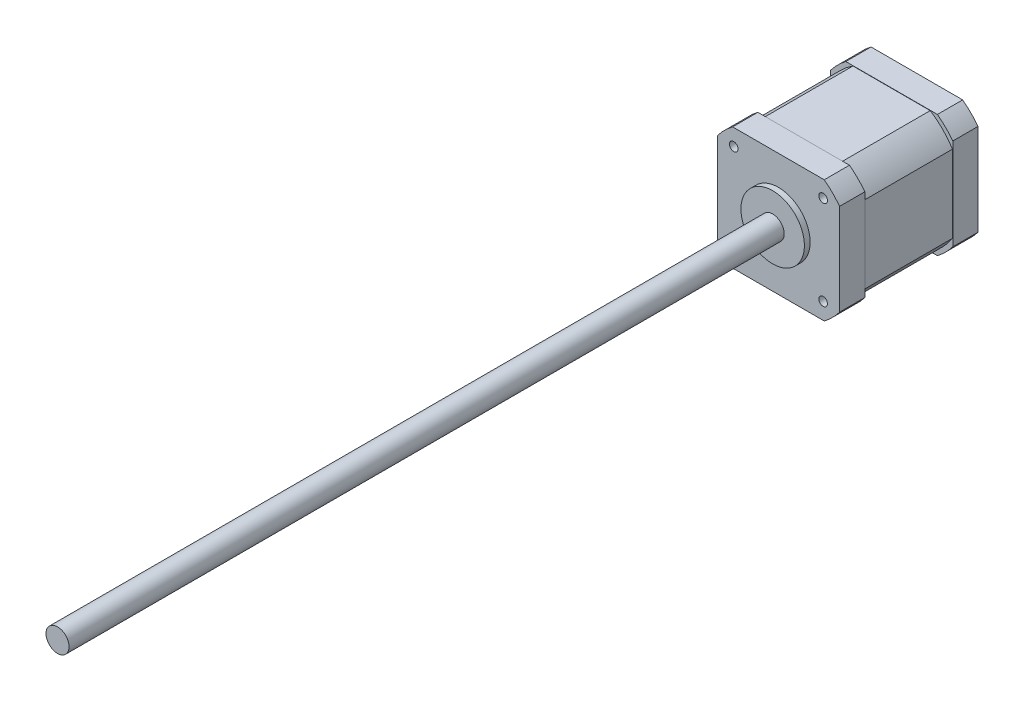
SolidWorks part; units mm, degrees
material "Plain Carbon Steel"
ref_plane "Front" through (0, 0, 0) normal (0, 0, 1) x (1, 0, 0)
ref_plane "Top" through (0, 0, 0) normal (0, 1, 0) x (1, 0, 0)
ref_plane "Right" through (0, 0, 0) normal (1, 0, 0) x (0, 0, -1)
sketch "Sketch1" plane through (0, 0, 0) normal (0, 0, 1) x (1, 0, 0)
  circle A0 centre (0, 0) radius 4
  dimension "D1" = 8
extrude "Boss-Extrude1" add sketch "Sketch1" along normal blind 250
sketch "Sketch2" plane through (0, 0, 0) normal (0, 0, -1) x (-1, 0, 0)
  circle A0 centre (0, 0) radius 11
  dimension "D1" = 22
extrude "Boss-Extrude2" add sketch "Sketch2" against normal blind 2
sketch "Sketch3" plane through (0, 0, 0) normal (0, 0, -1) x (-1, 0, 0)
  line L1 (21.209, -21.209) -> (-21.209, -21.209)
  line L2 (21.209, -21.209) -> (21.209, 21.209)
  line L3 (21.209, 21.209) -> (-21.209, 21.209)
  line L4 (-21.209, -21.209) -> (-21.209, 21.209)
  line L5 (21.209, -21.209) -> (-21.209, 21.209) construction
  line L6 (21.209, 21.209) -> (-21.209, -21.209) construction
  point P0 (0, 0)
  dimension "D1" = 42.418
extrude "Boss-Extrude3" add sketch "Sketch3" along normal blind 48
sketch "Sketch4" plane through (0, 0, -48) normal (0, 0, -1) x (-1, 0, 0)
  line L0 (-21.209, -15.888) -> (-21.209, -21.209)
  line L1 (15.888, -21.209) -> (21.209, -21.209)
  line L2 (21.209, 15.888) -> (21.209, 21.209)
  line L3 (-15.888, 21.209) -> (-21.209, 21.209)
  line L4 (-21.209, 21.209) -> (-21.209, -21.209)
  line L5 (-21.209, -21.209) -> (21.209, -21.209)
  line L6 (21.209, -21.209) -> (21.209, 21.209)
  line L7 (21.209, 21.209) -> (-21.209, 21.209)
  line L8 (-21.209, 21.209) -> (-21.209, 15.888)
  line L9 (-21.209, -21.209) -> (-15.888, -21.209)
  line L10 (21.209, -21.209) -> (21.209, -15.888)
  line L11 (21.209, 21.209) -> (15.888, 21.209)
  arc A0 (-21.209, -15.888) -> (-15.888, -21.209) centre (0, 0) ccw
  arc A1 (15.888, -21.209) -> (21.209, -15.888) centre (0, 0) ccw
  arc A2 (21.209, 15.888) -> (15.888, 21.209) centre (0, 0) ccw
  arc A3 (-15.888, 21.209) -> (-21.209, 15.888) centre (0, 0) ccw
  dimension "D2" = 26.5
  dimension "D1" = 0
extrude "Cut-Extrude1" cut sketch "Sketch4" against normal through all
hole_wizard "M3x0.5 Tapped Hole1" positions "Sketch6" profile "Sketch5" tap size "M3x0.5" standard "ANSI Metric"
sketch "Sketch6" plane through (0, 0, 0) normal (0, 0, 1) x (1, 0, 0)
  line L0 (-16.1632, 0) -> (0, 0) construction
  line L1 (0, 0) -> (0, 15.0764) construction
  point P0 (-15.5, 15.5)
  point P11 (-15.5, -15.5)
  point P12 (15.5, -15.5)
  point P13 (15.5, 15.5)
  dimension "D1" = 31
  dimension "D2" = 31
sketch "Sketch5" plane through (-15.5, 15.5, 0) normal (1, 0, 0) x (0, -1, 0)
  line L0 (0, 0) -> (0, 8.2511)
  line L1 (0, 8.2511) -> (1.25, 7.5)
  line L2 (1.25, 7.5) -> (1.25, 6)
  line L3 (1.25, 6) -> (1.5, 6)
  line L4 (1.5, 6) -> (1.5, 0)
  line L5 (1.5, 0) -> (0, 0)
  line L10 (0, 8.2511) -> (-1.25, 7.5) construction
  line L11 (0, -6.35) -> (0, 107.95) construction
  dimension "Tap Drill Dia." = 2.5
  dimension "Tap Drill Depth" = 7.5
  dimension "Thread Major Dia." = 3
  dimension "Thread Depth" = 6
  dimension "Drill Angle" = 118
ref_plane "Plane1" through (0, 0, -24) normal (0, 0, 1) x (1, 0, 0)
sketch "Sketch8" plane through (0, 0, -24) normal (0, 0, 1) x (1, 0, 0)
  line L0 (-13.3944, 21.109) -> (13.3944, 21.109)
  line L1 (-5.7152, 0) -> (0, 0) construction
  line L2 (0, 0) -> (0, 8.4579) construction
  line L3 (-15.888, 21.209) -> (15.888, 21.209) construction
  line L4 (-13.3944, -21.109) -> (13.3944, -21.109)
  line L5 (-21.109, 13.3944) -> (-21.109, -13.3944)
  line L6 (-21.209, -15.888) -> (-21.209, 15.888) construction
  line L7 (21.109, 13.3944) -> (21.109, -13.3944)
  line L12 (15.888, 21.209) -> (-15.888, 21.209)
  line L13 (-21.209, 15.888) -> (-21.209, -15.888)
  line L14 (-15.888, -21.209) -> (15.888, -21.209)
  line L15 (21.209, -15.888) -> (21.209, 15.888)
  line L16 (15.888, 21.209) -> (-15.888, 21.209)
  line L17 (-21.209, 15.888) -> (-21.209, -15.888)
  line L18 (-15.888, -21.209) -> (15.888, -21.209)
  line L19 (21.209, -15.888) -> (21.209, 15.888)
  arc A0 (-13.3944, 21.109) -> (-21.109, 13.3944) centre (0, 0) ccw
  arc A1 (-21.109, -13.3944) -> (-13.3944, -21.109) centre (0, 0) ccw
  arc A2 (21.109, 13.3944) -> (13.3944, 21.109) centre (0, 0) ccw
  arc A3 (13.3944, -21.109) -> (21.109, -13.3944) centre (0, 0) ccw
  arc A5 (-15.888, 21.209) -> (-21.209, 15.888) centre (0, 0) ccw
  arc A6 (-21.209, -15.888) -> (-15.888, -21.209) centre (0, 0) ccw
  arc A7 (15.888, -21.209) -> (21.209, -15.888) centre (0, 0) ccw
  arc A8 (21.209, 15.888) -> (15.888, 21.209) centre (0, 0) ccw
  arc A9 (-15.888, 21.209) -> (-21.209, 15.888) centre (0, 0) ccw
  arc A10 (-21.209, -15.888) -> (-15.888, -21.209) centre (0, 0) ccw
  arc A11 (15.888, -21.209) -> (21.209, -15.888) centre (0, 0) ccw
  arc A12 (21.209, 15.888) -> (15.888, 21.209) centre (0, 0) ccw
  dimension "D1" = 50
  dimension "D2" = 0.1
  dimension "D3" = 0.1
  dimension "D4" = 0
extrude "Cut-Extrude3" cut sketch "Sketch8" against normal mid plane 30.5
